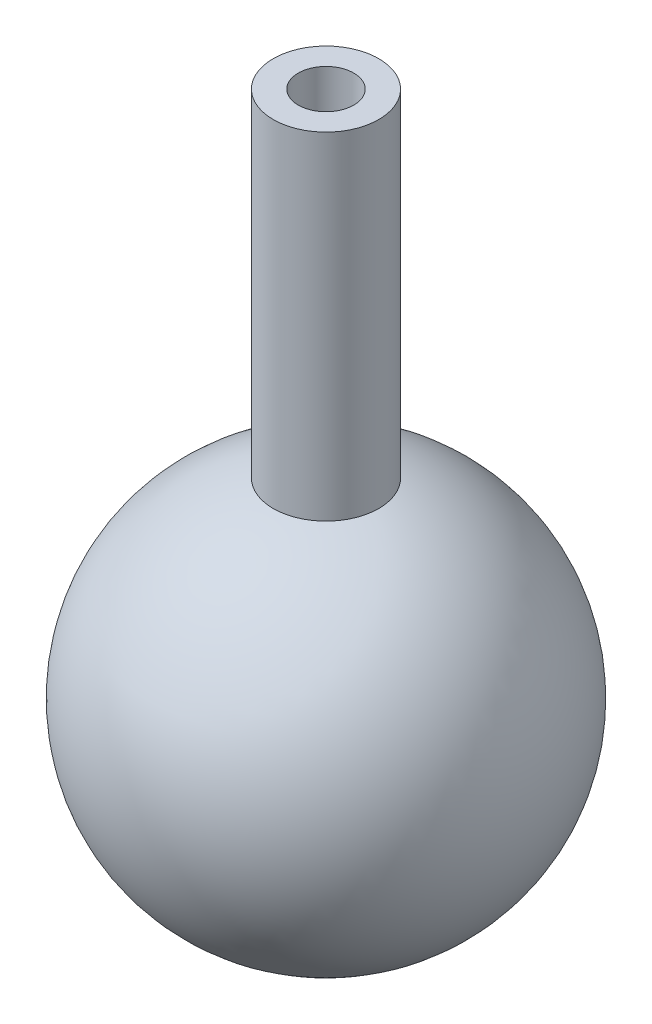
SolidWorks part; units mm, degrees
ref_plane "Front Plane" through (0, 0, 0) normal (0, 0, 1) x (1, 0, 0)
ref_plane "Top Plane" through (0, 0, 0) normal (0, 1, 0) x (1, 0, 0)
ref_plane "Right Plane" through (0, 0, 0) normal (1, 0, 0) x (0, 0, -1)
other "Center of Mass"
sketch "Sketch1" plane through (0, 0, 0) normal (0, 1, 0) x (1, 0, 0)
  line L0 (0, 30) -> (0, -30)
  arc A0 (0, -30) -> (0, 30) centre (0, 0) ccw
  point P6 (0, 0)
  dimension "D1" = 60
revolve "Revolve1" add sketch "Sketch1" angle 360 about L0
ref_plane "Plane1" through (0, 30, 0) normal (0, 1, 0) x (1, 0, 0)
sketch "Sketch2" plane through (0, 30, 0) normal (0, 1, 0) x (1, 0, 0)
  circle A0 centre (0, 0) radius 8
extrude "Boss-Extrude1" add sketch "Sketch2" along normal blind 50 and the other way blind 10
sketch "Sketch4" plane through (0, 80, 0) normal (0, 1, 0) x (1, 0, 0)
  circle A0 centre (0, 0) radius 4.21
  dimension "D1" = 8.42
extrude "Cut-Extrude3" cut sketch "Sketch4" against normal blind 50
ref_plane "Plane2" through (0, 0, 0) normal (0, 1, 0) x (1, 0, 0)
sketch "Sketch5" plane through (0, 0, 0) normal (0, 1, 0) x (1, 0, 0)
  line L0 (30, 0) -> (-30, 0) construction
  line L1 (0, -30) -> (0, 30) construction
  circle A0 centre (0, 0) radius 30 construction
  point P7 (0, 0)
  point P11 (0, 0)
